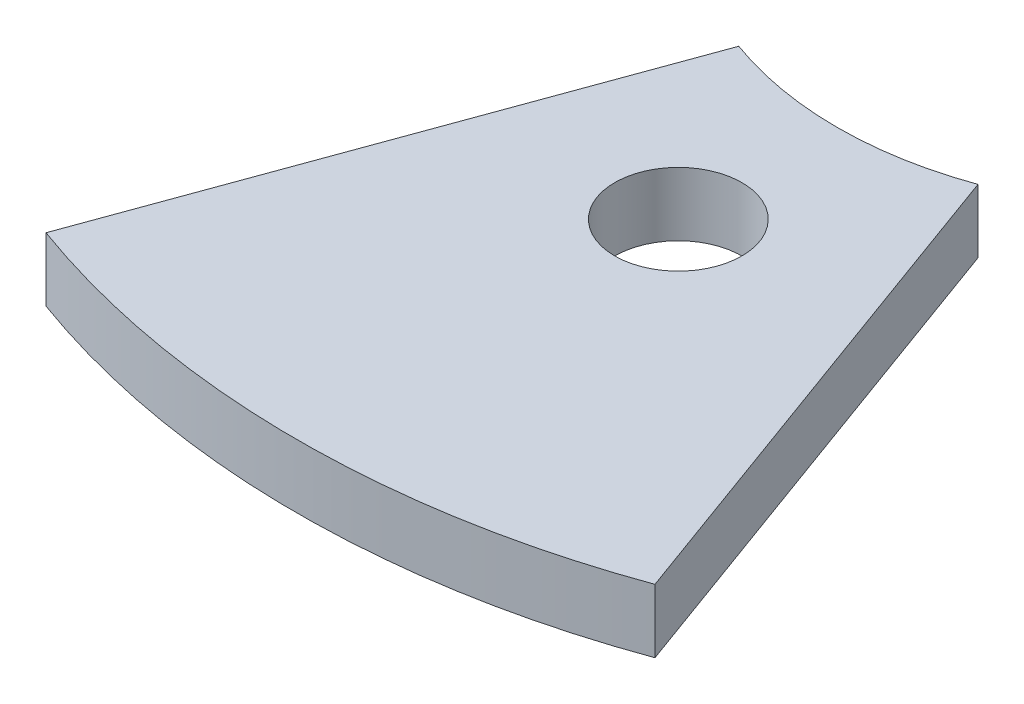
SolidWorks part; units mm, degrees
ref_plane "Front Plane" through (0, 0, 0) normal (0, 0, 1) x (1, 0, 0)
ref_plane "Top Plane" through (0, 0, 0) normal (0, 1, 0) x (1, 0, 0)
ref_plane "Right Plane" through (0, 0, 0) normal (1, 0, 0) x (0, 0, -1)
sketch "Sketch1" plane through (0, 0, 0) normal (0, 1, 0) x (1, 0, 0)
  line L0 (0, 50.8) -> (-30.4056, -32.7387)
  line L1 (0, 50.8) -> (0, 0) construction
  line L2 (0, 50.8) -> (30.4056, -32.7387)
  circle A0 centre (0, 0) radius 6.35
  circle A1 centre (0, 50.8) radius 88.9
  circle A2 centre (0, 50.8) radius 34.925
  point P3 (0, 50.8)
  dimension "D1" = 20
  dimension "D3" = 69.85
  dimension "D4" = 177.8
  dimension "D2" = 50.8
extrude "Boss-Extrude1" add sketch "Sketch1" along normal blind 6.35
